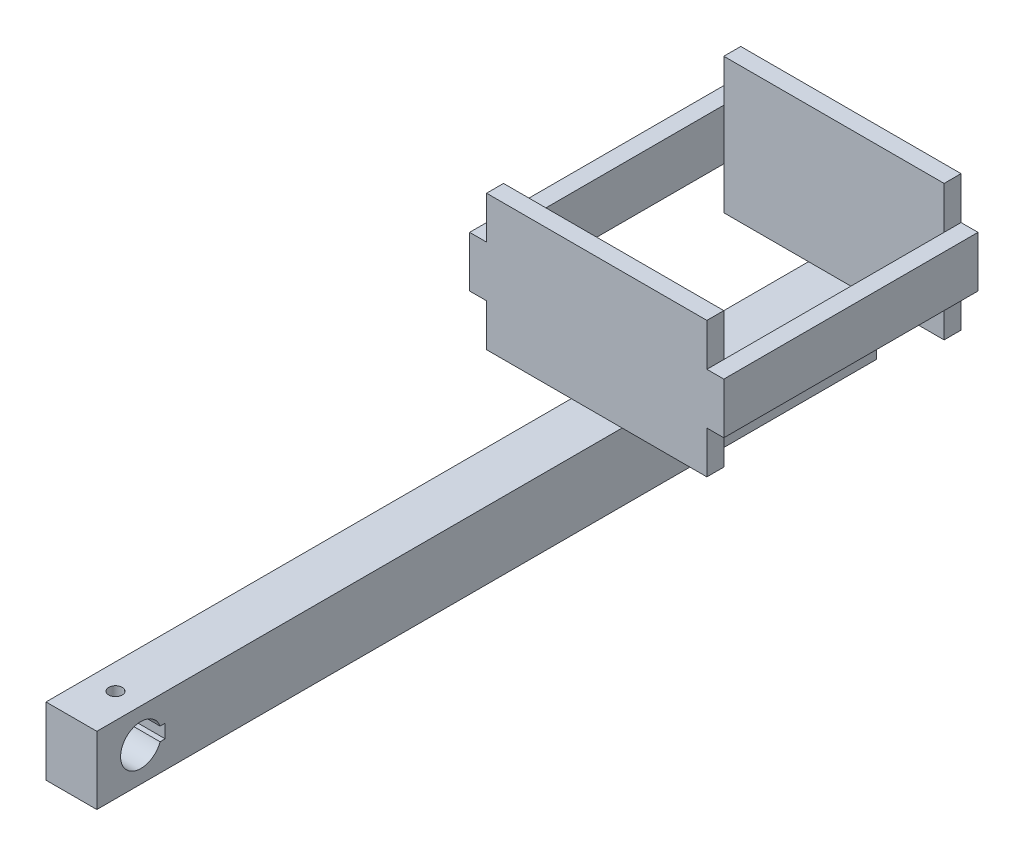
SolidWorks part; units mm, degrees
ref_plane "Front Plane" through (0, 0, 0) normal (0, 0, 1) x (1, 0, 0)
ref_plane "Top Plane" through (0, 0, 0) normal (0, 1, 0) x (1, 0, 0)
ref_plane "Right Plane" through (0, 0, 0) normal (1, 0, 0) x (0, 0, -1)
sketch "Sketch1" plane through (0, 0, 0) normal (0, 0, 1) x (1, 0, 0)
  line L1 (-7.5, 10) -> (7.5, 10)
  line L2 (-7.5, 10) -> (-7.5, -10)
  line L3 (-7.5, -10) -> (7.5, -10)
  line L4 (7.5, 10) -> (7.5, -10)
  line L5 (-7.5, 10) -> (7.5, -10) construction
  line L6 (-7.5, -10) -> (7.5, 10) construction
  point P0 (0, 0)
  dimension "D1" = 15
  dimension "D2" = 20
extrude "Boss-Extrude1" add sketch "Sketch1" along normal blind 230
sketch "Sketch2" plane through (0, 0, 0) normal (0, 0, -1) x (-1, 0, 0)
  line L1 (-32.5, 10) -> (32.5, 10)
  line L2 (-32.5, 10) -> (-32.5, 50)
  line L3 (-32.5, 50) -> (32.5, 50)
  line L4 (32.5, 10) -> (32.5, 50)
  line L6 (-7.5, 10) -> (7.5, 10) construction
  point P4 (0, 10)
  point P10 (0, 10)
  dimension "D1" = 65
  dimension "D2" = 40
extrude "Boss-Extrude6" add sketch "Sketch2" against normal blind 5
sketch "Sketch7" plane through (32.5, 0, 0) normal (1, 0, 0) x (0, 0, -1)
  line L0 (0, 50) -> (0, 10) construction
  line L1 (0, 37.5) -> (-75, 37.5)
  line L2 (0, 37.5) -> (0, 22.5)
  line L3 (0, 22.5) -> (-75, 22.5)
  line L4 (-75, 37.5) -> (-75, 22.5)
  point P4 (0, 30)
  point P7 (0, 30)
  dimension "D1" = 15
  dimension "D2" = 75
extrude "Boss-Extrude7" add sketch "Sketch7" along normal blind 5
sketch "Sketch8" plane through (-32.5, 0, 0) normal (-1, 0, 0) x (0, 0, 1)
  line L1 (0, 37.5) -> (75, 37.5)
  line L2 (0, 37.5) -> (0, 22.5)
  line L3 (0, 22.5) -> (75, 22.5)
  line L4 (75, 37.5) -> (75, 22.5)
extrude "Boss-Extrude8" add sketch "Sketch8" along normal blind 5
sketch "Sketch9" plane through (0, 0, 75) normal (0, 0, 1) x (1, 0, 0)
  line L1 (-32.5, 50) -> (32.5, 50)
  line L2 (-32.5, 50) -> (-32.5, 10)
  line L3 (-32.5, 10) -> (32.5, 10)
  line L4 (32.5, 50) -> (32.5, 10)
extrude "Boss-Extrude11" add sketch "Sketch9" against normal blind 5
sketch "Sketch10" plane through (-7.5, 0, 0) normal (-1, 0, 0) x (0, 0, 1)
  line L0 (230, 10) -> (230, -10) construction
  line L2 (209.8431, 2) -> (211.3431, 2)
  line L3 (209.8431, 2) -> (209.8431, -2)
  line L4 (209.8431, -2) -> (211.3431, -2)
  line L6 (209.8431, 2) -> (211, 0) construction
  line L7 (209.8431, -2) -> (211, 0) construction
  arc A0 (211.3431, -2) -> (211.3431, 2) centre (217, 0) ccw
  point P4 (230, 0)
  point P5 (211, 0)
  point P11 (209.8431, 0)
  dimension "D1" = 12
  dimension "D2" = 13
  dimension "D3" = 1.5
  dimension "D4" = 4
extrude "Cut-Extrude1" cut sketch "Sketch10" against normal through all
sketch "Sketch11" plane through (0, 0, 0) normal (1, 0, 0) x (0, 0, -1)
  point P0 (-217, 0)
sketch "Sketch12" plane through (0, 10, 0) normal (0, 1, 0) x (1, 0, 0)
  line L1 (7.5, -5) -> (-7.5, -5) construction
  point P0 (0, -37.5)
  dimension "D1" = 32.5
sketch "Sketch13" plane through (0, 10, 0) normal (0, 1, 0) x (1, 0, 0)
  circle A0 centre (0, -217) radius 1.9844
  dimension "D1" = 3.9688
extrude "Cut-Extrude2" cut sketch "Sketch13" against normal blind 10
